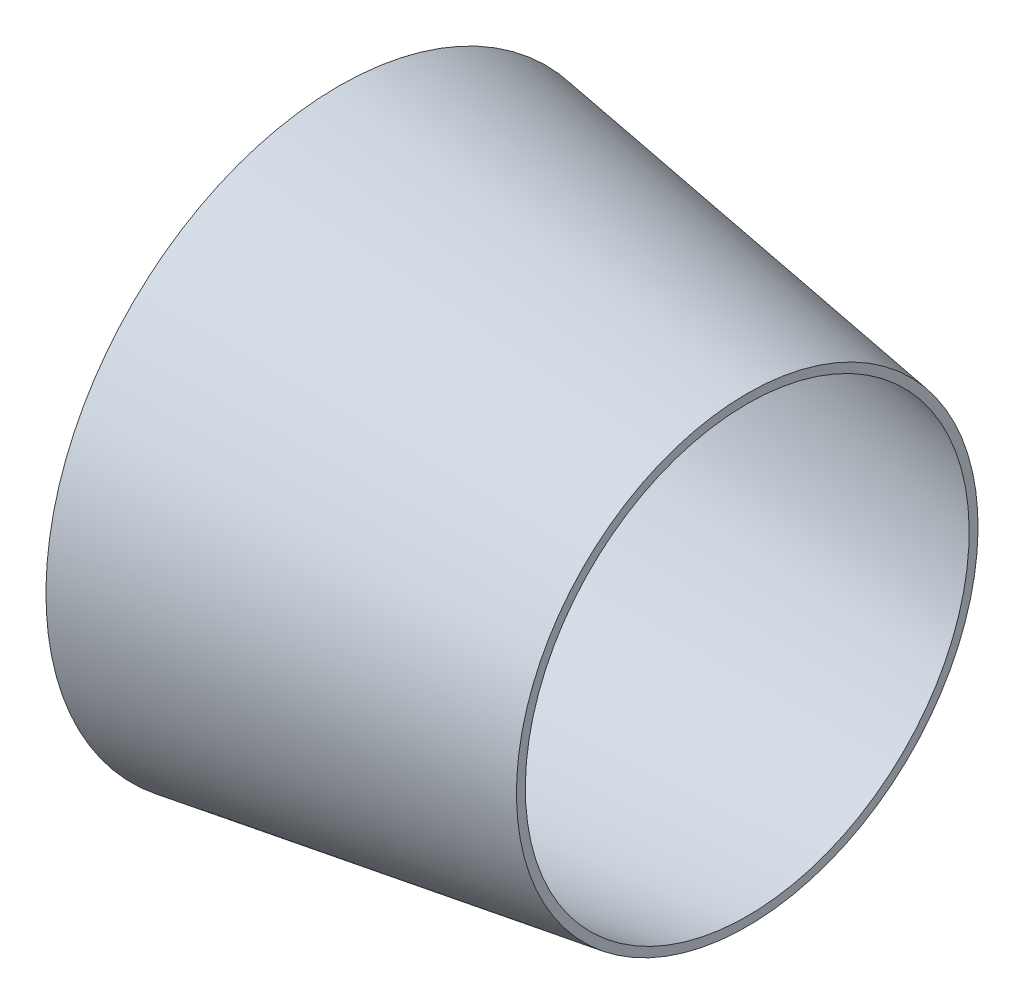
SolidWorks part; units mm, degrees
ref_plane "Front Plane" through (0, 0, 0) normal (0, 0, 1) x (1, 0, 0)
ref_plane "Top Plane" through (0, 0, 0) normal (0, 1, 0) x (1, 0, 0)
ref_plane "Right Plane" through (0, 0, 0) normal (1, 0, 0) x (0, 0, -1)
sketch "Sketch1" plane through (0, 0, 0) normal (0, 0, 1) x (1, 0, 0)
  line L0 (0, 0) -> (6000, 0) construction
  line L1 (3200, 1550) -> (3200, 1650)
  line L2 (3200, 1650) -> (5500, 1300)
  line L3 (5500, 1300) -> (5500, 1250)
  line L4 (5500, 1250) -> (3200, 1550)
revolve "Revolve1" add sketch "Sketch1" angle 360 about L0
